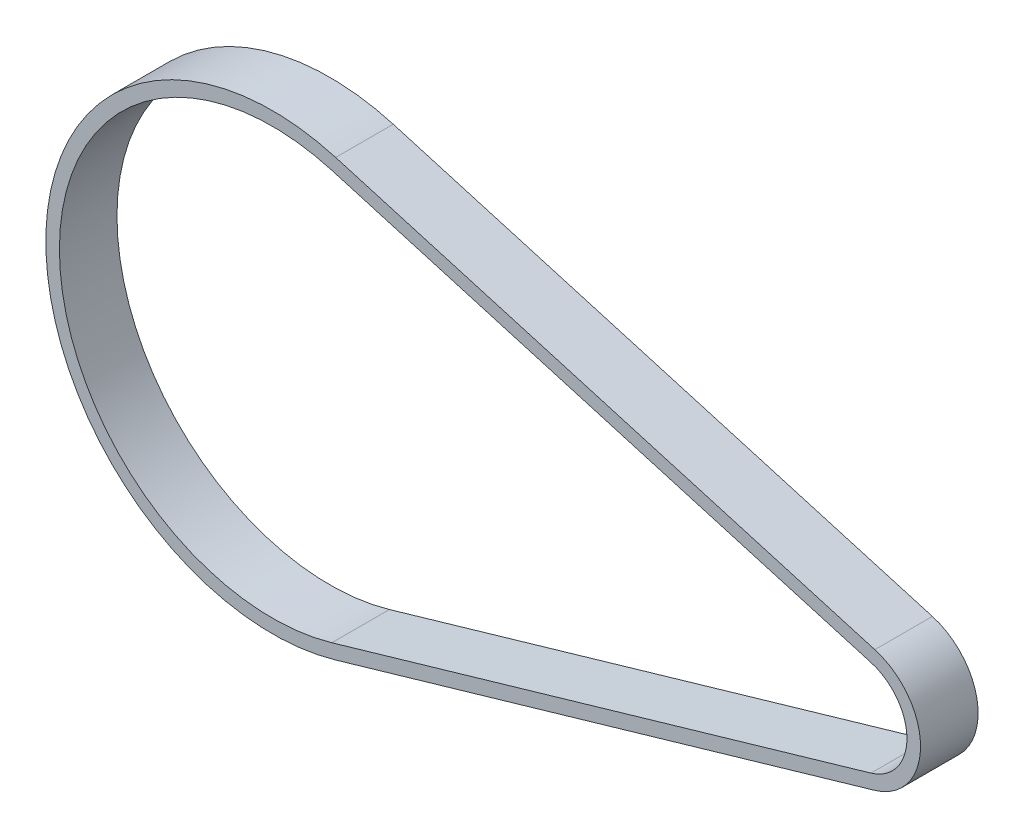
SolidWorks part; units mm, degrees
ref_plane "Front" through (0, 0, 0) normal (0, 0, 1) x (1, 0, 0)
ref_plane "Top" through (0, 0, 0) normal (0, 1, 0) x (1, 0, 0)
ref_plane "Right" through (0, 0, 0) normal (1, 0, 0) x (0, 0, -1)
sketch "Sketch1" plane through (0, 0, 0) normal (0, 0, 1) x (1, 0, 0)
  line L0 (-287.6953, 107.8388) -> (-168.7418, 73.269)
  line L1 (-287.6953, 11.8117) -> (-168.7418, 46.3815)
  line L2 (-288.5325, 104.958) -> (-169.579, 70.3882)
  line L3 (-288.5325, 14.6925) -> (-169.579, 49.2623)
  arc A0 (-287.6953, 107.8388) -> (-287.6953, 11.8117) centre (-301.6488, 59.8253) ccw
  arc A1 (-168.7418, 46.3815) -> (-168.7418, 73.269) centre (-172.6488, 59.8253) ccw
  arc A2 (-169.579, 49.2623) -> (-169.579, 70.3882) centre (-172.6488, 59.8253) ccw
  arc A3 (-288.5325, 104.958) -> (-288.5325, 14.6925) centre (-301.6488, 59.8253) ccw
extrude "Boss-Extrude1" add sketch "Sketch1" along normal blind 12.7
